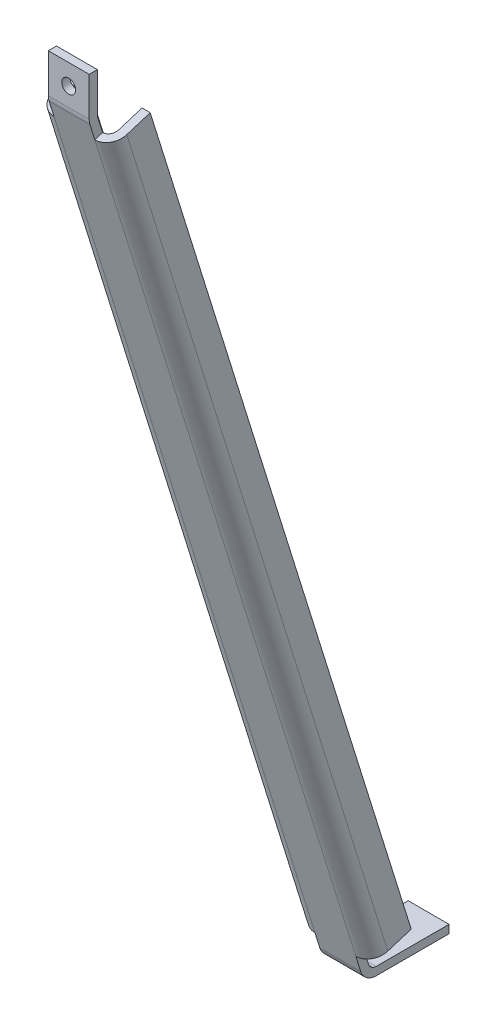
SolidWorks part; units mm, degrees
other "Roof Support Arm 3 Left"
ref_plane "Front Plane" through (0, 0, 0) normal (0, 0, 1) x (1, 0, 0)
ref_plane "Top Plane" through (0, 0, 0) normal (0, 1, 0) x (1, 0, 0)
ref_plane "Right Plane" through (0, 0, 0) normal (1, 0, 0) x (0, 0, -1)
sketch3d "Formed Web Section Sketch datum points"
  point P0 (185, 0, 0)
  point P1 (185, 10, 0)
  point P2 (185, 0, 10)
ref_plane "Formed Web Section Sketch plane" through (185, 0, 0) normal (1, 0, 0) x (0, 0, -1)
sketch "Formed Web Section Sketch" plane through (185, 0, 0) normal (1, 0, 0) x (0, 0, -1)
  line L0 (-22, 64) -> (-39.7926, 64)
  line L1 (-43.6115, 66.8099) -> (-109.8189, 279.2665)
  line L2 (-110, 280.4566) -> (-110, 290)
  line L3 (-110, 290) -> (-108, 290)
  line L4 (-108, 290) -> (-108, 280.4566)
  line L5 (-107.9094, 279.8616) -> (-41.702, 67.405)
  line L6 (-39.7926, 66) -> (-22, 66)
  line L7 (-22, 66) -> (-22, 64)
  arc A0 (-43.6115, 66.8099) -> (-39.7926, 64) centre (-39.7926, 68) ccw
  arc A1 (-110, 280.4566) -> (-109.8189, 279.2665) centre (-106, 280.4566) ccw
  arc A2 (-108, 280.4566) -> (-107.9094, 279.8616) centre (-106, 280.4566) ccw
  arc A3 (-41.702, 67.405) -> (-39.7926, 66) centre (-39.7926, 68) ccw
extrude "Formed Web" add sketch "Formed Web Section Sketch" along normal blind 10 separate body
sketch3d "Edge Lip Sketch datum points"
  point P0 (190, 70.9263, 43.8468)
  point P1 (200, 70.9263, 43.8468)
  point P2 (190, 67.9512, 53.394)
ref_plane "Edge Lip Sketch plane" through (0, 77.1026, 24.0273) normal (0, -0.9547, -0.2975) x (-1, 0, 0)
sketch "Edge Lip Sketch" plane through (0, 77.1026, 24.0273) normal (0, -0.9547, -0.2975) x (-1, 0, 0)
  line L0 (-181, -17.7595) -> (-181, -11.7595)
  line L1 (-181, -11.7595) -> (-183, -11.7595)
  line L2 (-183, -11.7595) -> (-183, -17.7595)
  line L3 (-185, -19.7595) -> (-185.1, -19.7595)
  line L4 (-185.1, -19.7595) -> (-185.1, -21.7595)
  line L5 (-185.1, -21.7595) -> (-185, -21.7595)
  line L6 (-199, -17.7595) -> (-199, -11.7595)
  line L7 (-199, -11.7595) -> (-197, -11.7595)
  line L8 (-197, -11.7595) -> (-197, -17.7595)
  line L9 (-195, -19.7595) -> (-194.9, -19.7595)
  line L10 (-194.9, -19.7595) -> (-194.9, -21.7595)
  line L11 (-194.9, -21.7595) -> (-195, -21.7595)
  arc A0 (-185, -21.7595) -> (-181, -17.7595) centre (-185, -17.7595) ccw
  arc A1 (-185, -19.7595) -> (-183, -17.7595) centre (-185, -17.7595) ccw
  arc A2 (-199, -17.7595) -> (-195, -21.7595) centre (-195, -17.7595) ccw
  arc A3 (-197, -17.7595) -> (-195, -19.7595) centre (-195, -17.7595) ccw
extrude "Edge Stiffening Lips" add sketch "Edge Lip Sketch" against normal blind 214.5337
sketch3d "Wall Mount Hole Sketch datum points"
  point P0 (0, 63.8, 0)
  point P1 (10, 63.8, 0)
  point P2 (0, 63.8, 10)
ref_plane "Wall Mount Hole Sketch plane" through (0, 63.8, 0) normal (0, -1, 0) x (-1, 0, 0)
sketch "Wall Mount Hole Sketch" plane through (0, 63.8, 0) normal (0, -1, 0) x (-1, 0, 0)
  circle A0 centre (-190, -29) radius 1.7
  circle A1 centre (-190, -36) radius 1.7
extrude "Wall Mount Holes" cut sketch "Wall Mount Hole Sketch" against normal blind 2.4
sketch3d "Cover Mount Hole Sketch datum points"
  point P0 (0, 0, 107.8)
  point P1 (10, 0, 107.8)
  point P2 (0, 10, 107.8)
ref_plane "Cover Mount Hole Sketch plane" through (0, 0, 107.8) normal (0, 0, 1) x (1, 0, 0)
sketch "Cover Mount Hole Sketch" plane through (0, 0, 107.8) normal (0, 0, 1) x (1, 0, 0)
  circle A0 centre (190, 285) radius 1.7
extrude "Cover Mount Hole" cut sketch "Cover Mount Hole Sketch" along normal blind 2.4
